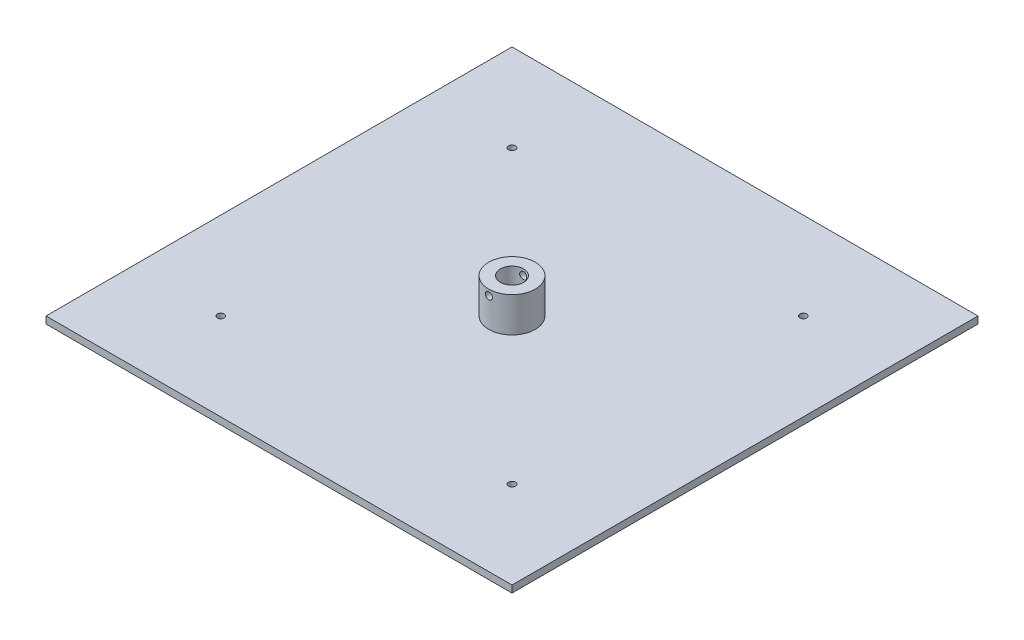
SolidWorks part; units mm, degrees
ref_plane "前视基准面" through (0, 0, 0) normal (0, 0, 1) x (1, 0, 0)
ref_plane "上视基准面" through (0, 0, 0) normal (0, 1, 0) x (1, 0, 0)
ref_plane "右视基准面" through (0, 0, 0) normal (1, 0, 0) x (0, 0, -1)
sketch "草图1" plane through (0, 0, 0) normal (0, 1, 0) x (1, 0, 0)
  line L0 (-200, 200) -> (200, -200) construction
  line L1 (-200, 200) -> (200, 200)
  line L2 (-200, 200) -> (-200, -200)
  line L3 (-200, -200) -> (200, -200)
  line L4 (200, 200) -> (200, -200)
  line L5 (-125, 125) -> (125, 125) construction
  line L6 (-125, 125) -> (-125, -125) construction
  line L7 (0, 36.622) -> (0, -40.3819) construction
  circle A0 centre (-125, 125) radius 3
  circle A1 centre (125, 125) radius 3
  circle A2 centre (125, -125) radius 3
  circle A3 centre (-125, -125) radius 3
  dimension "D3" = 6
  dimension "D1" = 400
  dimension "D2" = 400
  dimension "D5" = 90
  dimension "D6" = 250
  dimension "D7" = 250
  dimension "D4" = 2
extrude "凸台-拉伸1" add sketch "草图1" along normal blind 6
sketch "草图2" plane through (0, 6, 0) normal (0, 1, 0) x (1, 0, 0)
  circle A0 centre (0, 0) radius 20
  dimension "D1" = 40
extrude "凸台-拉伸2" add sketch "草图2" along normal blind 30
sketch "草图3" plane through (0, 36, 0) normal (0, 1, 0) x (1, 0, 0)
  circle A0 centre (0, 0) radius 10
  dimension "D1" = 20
extrude "切除-拉伸1" cut sketch "草图3" against normal through all
ref_plane "基准面4" through (0, 0, -20) normal (0, 0, -1) x (-1, 0, 0)
sketch "草图4" plane through (0, 0, -20) normal (0, 0, -1) x (-1, 0, 0)
  line L0 (-200, 6) -> (-200, 0) construction
  line L1 (-200, 6) -> (200, 6) construction
  circle A0 centre (0, 31) radius 3
  dimension "D1" = 6
  dimension "D2" = 200
  dimension "D3" = 25
extrude "切除-拉伸2" cut sketch "草图4" against normal through all contours A0
